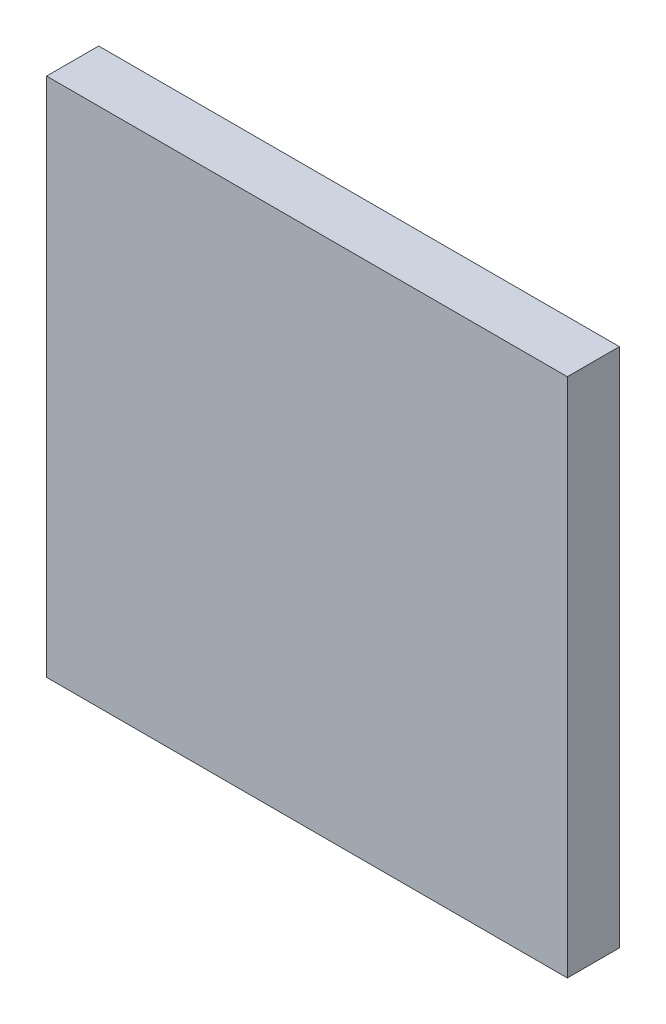
SolidWorks part; units mm, degrees
material "Pino"
ref_plane "Alzado" through (0, 0, 0) normal (0, 0, 1) x (1, 0, 0)
ref_plane "Planta" through (0, 0, 0) normal (0, 1, 0) x (1, 0, 0)
ref_plane "Vista lateral" through (0, 0, 0) normal (1, 0, 0) x (0, 0, -1)
sketch "Croquis1" plane through (0, 0, 0) normal (0, 0, 1) x (1, 0, 0)
  line L1 (-43.1973, 28.4014) -> (106.8027, 28.4014)
  line L2 (-43.1973, 28.4014) -> (-43.1973, -121.5986)
  line L3 (-43.1973, -121.5986) -> (106.8027, -121.5986)
  line L4 (106.8027, 28.4014) -> (106.8027, -121.5986)
  dimension "D1" = 150
  dimension "D2" = 150
extrude "Saliente-Extruir1" add sketch "Croquis1" along normal blind 15
